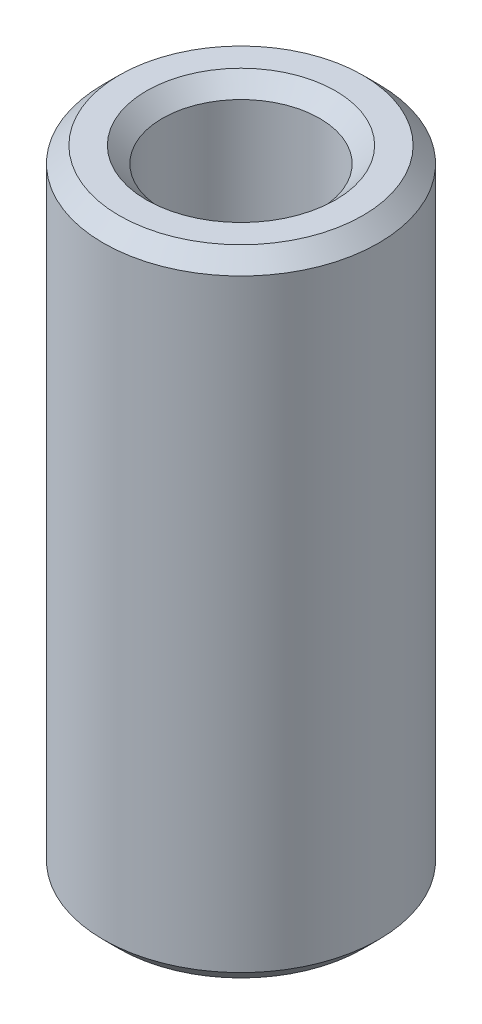
SolidWorks part; units mm, degrees
material "ABS"
ref_plane "Alzado" through (0, 0, 0) normal (0, 0, 1) x (1, 0, 0)
ref_plane "Planta" through (0, 0, 0) normal (0, 1, 0) x (1, 0, 0)
ref_plane "Vista lateral" through (0, 0, 0) normal (1, 0, 0) x (0, 0, -1)
sketch "Croquis1" plane through (0, 0, 0) normal (0, 1, 0) x (1, 0, 0)
  circle A0 centre (0, 0) radius 3.715
  circle A1 centre (0, 0) radius 6.5
  dimension "D1" = 7.43
  dimension "D2" = 13
extrude "Saliente-Extruir1" add sketch "Croquis1" along normal mid plane 30
chamfer "Chaflán1" distance 0.75 angle 45 4 edges at (0, 15, 3.715) (0, -15, 3.715) (0, -15, 6.5) (0, 15, 6.5)
